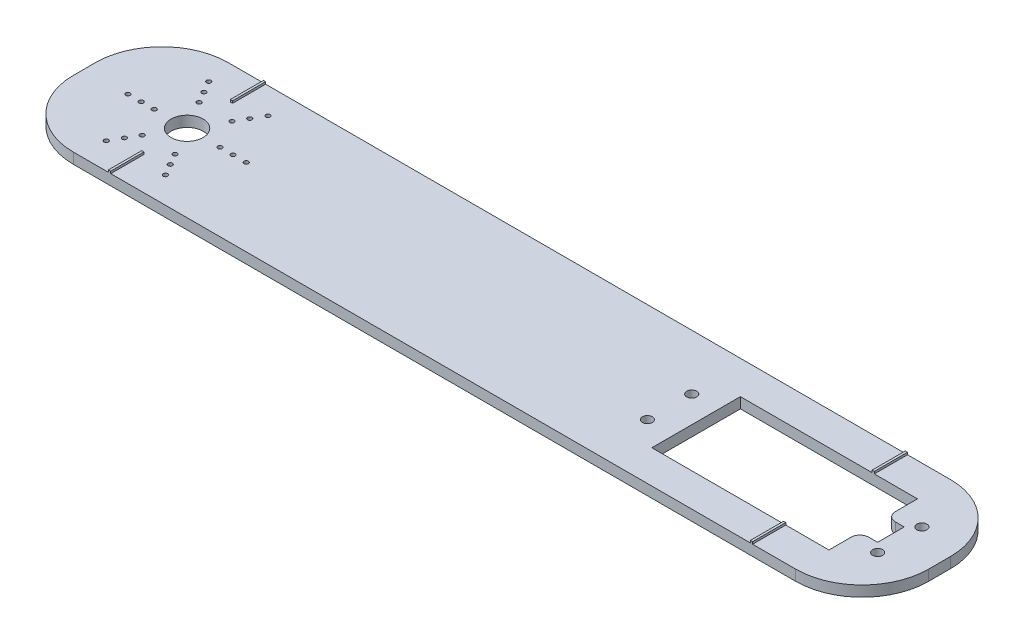
SolidWorks part; units mm, degrees
ref_plane "Front Plane" through (0, 0, 0) normal (0, 0, 1) x (1, 0, 0)
ref_plane "Top Plane" through (0, 0, 0) normal (0, 1, 0) x (1, 0, 0)
ref_plane "Right Plane" through (0, 0, 0) normal (1, 0, 0) x (0, 0, -1)
sketch "Sketch1" plane through (0, 0, 0) normal (0, 1, 0) x (1, 0, 0)
  line L1 (-65.6771, 38.9958) -> (127.5229, 38.9958)
  line L2 (-65.6771, 38.9958) -> (-65.6771, 3.9958)
  line L3 (-65.6771, 3.9958) -> (127.5229, 3.9958)
  line L4 (127.5229, 38.9958) -> (127.5229, 3.9958)
  dimension "D1" = 193.2
  dimension "D2" = 35
extrude "Boss-Extrude1" add sketch "Sketch1" along normal blind 2.4
sketch "Sketch2" plane through (0, 2.4, 0) normal (0, 1, 0) x (1, 0, 0)
  line L0 (-42.4771, 38.9958) -> (-42.4771, 2.4158) construction
  line L1 (127.5229, 38.9958) -> (-65.6771, 38.9958) construction
  line L2 (-65.6771, 21.4958) -> (127.5229, 21.4958) construction
  line L3 (-65.6771, 38.9958) -> (-65.6771, 3.9958) construction
  line L4 (127.5229, 3.9958) -> (127.5229, 38.9958) construction
  line L5 (112.5229, 38.9958) -> (112.5229, 3.9958) construction
  line L6 (-65.6771, 3.9958) -> (127.5229, 3.9958) construction
  line L7 (72.5229, 38.9958) -> (72.5229, 3.9958) construction
  line L9 (72.5229, 31.4958) -> (112.5229, 31.4958)
  line L10 (72.5229, 31.4958) -> (72.5229, 11.4958)
  line L11 (72.5229, 11.4958) -> (112.5229, 11.4958)
  line L12 (112.5229, 31.4958) -> (112.5229, 11.4958)
  circle A0 centre (66.5229, 26.4958) radius 1.13
  circle A1 centre (118.5229, 26.4958) radius 1.13
  circle A2 centre (118.5229, 16.4958) radius 1.13
  circle A3 centre (66.5229, 16.4958) radius 1.13
  circle A4 centre (-42.4771, 21.4958) radius 3.625
  circle A5 centre (-49.9071, 21.4958) radius 0.5
  circle A6 centre (-52.8421, 21.4958) radius 0.5
  circle A7 centre (-55.8471, 21.4958) radius 0.5
  circle A8 centre (-49.1621, 33.0745) radius 0.5
  circle A9 centre (-47.6596, 30.4721) radius 0.5
  circle A10 centre (-46.1921, 27.9303) radius 0.5
  circle A11 centre (-35.7921, 33.0745) radius 0.5
  circle A12 centre (-37.2946, 30.4721) radius 0.5
  circle A13 centre (-38.7621, 27.9303) radius 0.5
  circle A14 centre (-29.1071, 21.4958) radius 0.5
  circle A15 centre (-32.1121, 21.4958) radius 0.5
  circle A16 centre (-35.0471, 21.4958) radius 0.5
  circle A17 centre (-35.7921, 9.917) radius 0.5
  circle A18 centre (-37.2946, 12.5194) radius 0.5
  circle A19 centre (-38.7621, 15.0612) radius 0.5
  circle A20 centre (-49.1621, 9.917) radius 0.5
  circle A21 centre (-47.6596, 12.5194) radius 0.5
  circle A22 centre (-46.1921, 15.0612) radius 0.5
  point P24 (-42.4771, 21.4958)
  point P37 (0, 0)
  point P70 (-42.4771, 21.4958)
  dimension "D5" = 2.26
  dimension "D6" = 2.26
  dimension "D11" = 7.25
  dimension "D12" = 7.43
  dimension "D13" = 10.365
  dimension "D14" = 13.37
  dimension "D15" = 1
  dimension "D16" = 1
  dimension "D17" = 1
  dimension "D19" = 20
  dimension "D1" = 23.2
  dimension "D2" = 15
  dimension "D3" = 40
  dimension "D4" = 10
  dimension "D7" = 5
  dimension "D8" = 6
  dimension "D9" = 5
  dimension "D10" = 6
  dimension "D18" = 6
extrude "Cut-Extrude1" cut sketch "Sketch2" against normal blind 2.4
sketch "Sketch4" plane through (0, 2.4, 0) normal (0, 1, 0) x (1, 0, 0)
  line L0 (72.5229, 21.4958) -> (127.5229, 21.4958) construction
  line L1 (72.5229, 31.4958) -> (72.5229, 11.4958) construction
  line L2 (127.5229, 3.9958) -> (127.5229, 38.9958) construction
  line L3 (112.5229, 11.4958) -> (112.5229, 31.4958) construction
  line L4 (112.5229, 24.4958) -> (116.5229, 24.4958)
  line L5 (112.5229, 24.4958) -> (112.5229, 18.4958)
  line L6 (112.5229, 18.4958) -> (116.5229, 18.4958)
  line L7 (116.5229, 24.4958) -> (116.5229, 18.4958)
  dimension "D1" = 6
  dimension "D2" = 3
  dimension "D3" = 4
extrude "Cut-Extrude2" cut sketch "Sketch4" against normal blind 2.4
fillet "Fillet1" radius 15 4 edges at (127.5229, 1.2, -38.9958) (127.5229, 1.2, -3.9958) (-65.6771, 1.2, -3.9958) (-65.6771, 1.2, -38.9958)
fillet "Fillet2" radius 2 2 edges at (112.5229, 1.2, -18.4958) (112.5229, 1.2, -24.4958)
sketch "Sketch5" plane through (0, 2.4, 0) normal (0, 1, 0) x (1, 0, 0)
  line L0 (-42.4771, 21.4958) -> (127.5229, 21.4958) construction
  line L1 (127.5229, 18.9958) -> (127.5229, 23.9958) construction
  line L2 (-42.4771, 38.9958) -> (-42.4771, 3.9958) construction
  line L3 (112.5229, 38.9958) -> (-50.6771, 38.9958) construction
  line L4 (-50.6771, 3.9958) -> (112.5229, 3.9958) construction
  line L5 (102.5229, 38.9958) -> (102.5229, 3.9958) construction
  line L6 (112.5229, 31.4958) -> (72.5229, 31.4958) construction
  line L7 (102.2729, 38.9958) -> (102.7729, 38.9958)
  line L8 (102.2729, 38.9958) -> (102.2729, 31.4958)
  line L9 (102.2729, 31.4958) -> (102.7729, 31.4958)
  line L10 (102.7729, 38.9958) -> (102.7729, 31.4958)
  line L11 (102.7729, 3.9958) -> (102.7729, 11.4958)
  line L12 (102.2729, 11.4958) -> (102.7729, 11.4958)
  line L13 (102.2729, 3.9958) -> (102.2729, 11.4958)
  line L14 (102.2729, 3.9958) -> (102.7729, 3.9958)
  line L15 (-42.2271, 3.9958) -> (-42.2271, 11.4958)
  line L16 (-42.7271, 38.9958) -> (-42.2271, 38.9958)
  line L17 (-42.7271, 38.9958) -> (-42.7271, 31.4958)
  line L18 (-42.7271, 31.4958) -> (-42.2271, 31.4958)
  line L19 (-42.2271, 38.9958) -> (-42.2271, 31.4958)
  line L20 (-42.7271, 11.4958) -> (-42.2271, 11.4958)
  line L21 (-42.7271, 3.9958) -> (-42.7271, 11.4958)
  line L22 (-42.7271, 3.9958) -> (-42.2271, 3.9958)
  dimension "D1" = 145
  dimension "D2" = 0.5
  dimension "D3" = 0.25
  dimension "D4" = 0.25
  dimension "D5" = 0.5
  dimension "D6" = 7.5
extrude "Boss-Extrude2" add sketch "Sketch5" along normal blind 0.5
